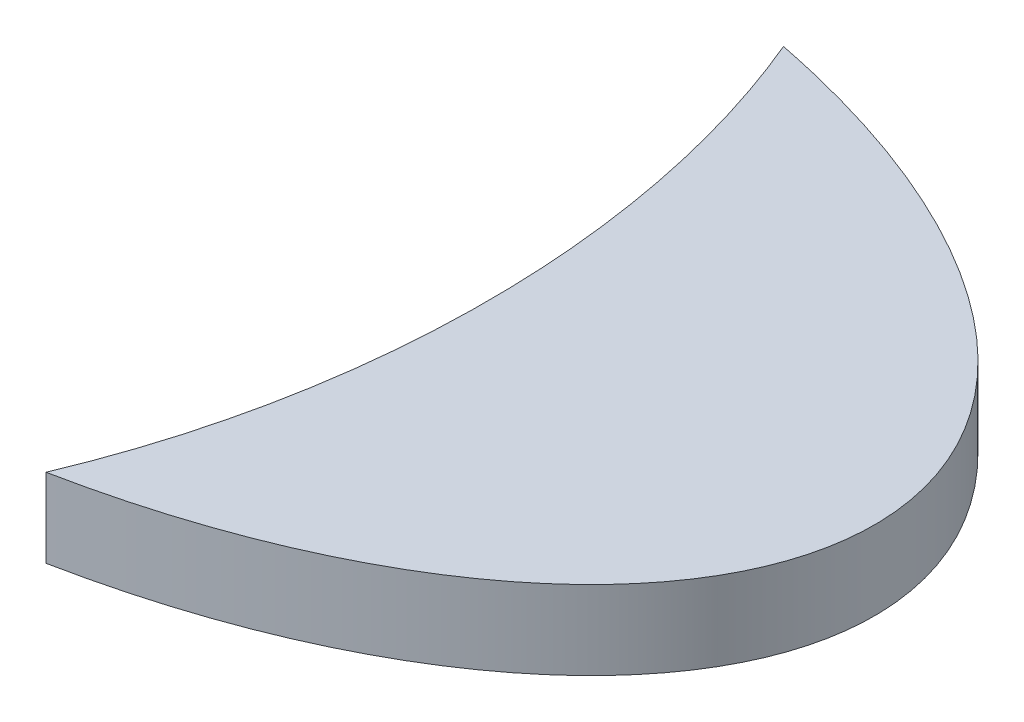
SolidWorks part; units mm, degrees
ref_plane "Front Plane" through (0, 0, 0) normal (0, 0, 1) x (1, 0, 0)
ref_plane "Top Plane" through (0, 0, 0) normal (0, 1, 0) x (1, 0, 0)
ref_plane "Right Plane" through (0, 0, 0) normal (1, 0, 0) x (0, 0, -1)
sketch "Sketch3" plane through (0, 0, 0) normal (0, 1, 0) x (1, 0, 0)
  ellipse E0 centre (0, 0) end of major axis (17.37, 0) minor radius 9.9
  ellipse E1 centre (-8.11, 0) end of major axis (-8.11, 19.88) minor radius 15.66
  dimension "D1" = 17.37
  dimension "D2" = 8.11
  dimension "D3" = 19.88
  dimension "D4" = 15.66
  dimension "D5" = 9.9
extrude "Boss-Extrude1" add sketch "Sketch3" along normal blind 2 contours E1 E0
